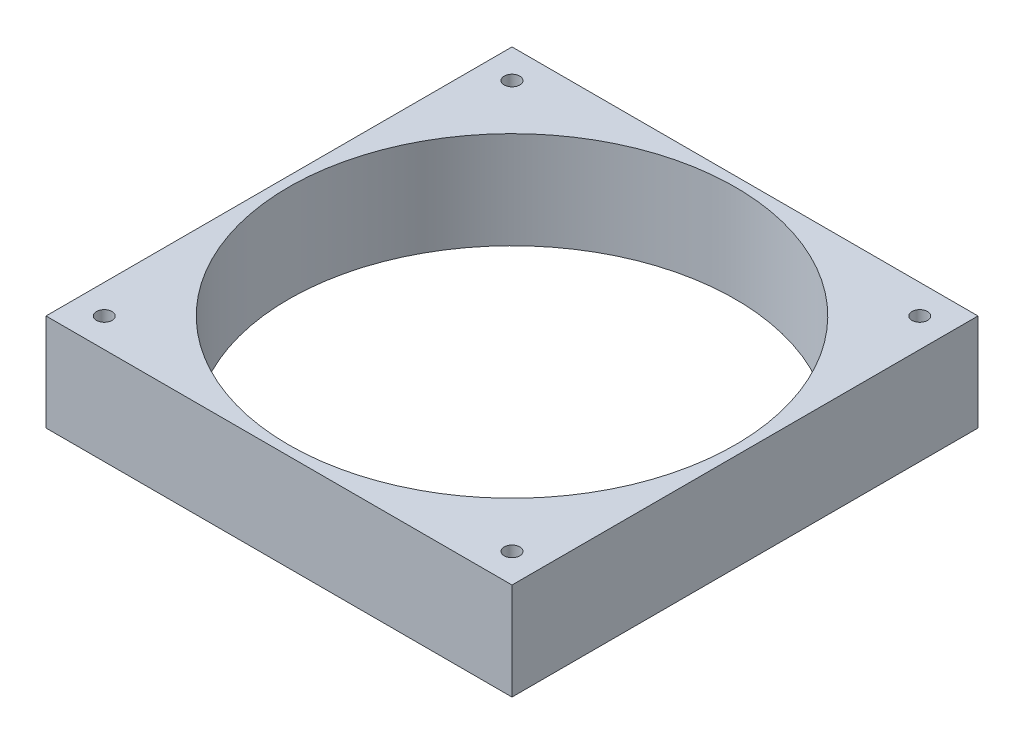
SolidWorks part; units mm, degrees
ref_plane "Front" through (0, 0, 0) normal (0, 0, 1) x (1, 0, 0)
ref_plane "Top" through (0, 0, 0) normal (0, 1, 0) x (1, 0, 0)
ref_plane "Right" through (0, 0, 0) normal (1, 0, 0) x (0, 0, -1)
sketch "Sketch1" plane through (0, 0, 0) normal (0, 1, 0) x (1, 0, 0)
  line L1 (0, 0) -> (120, 0)
  line L2 (0, 0) -> (0, -120)
  line L3 (0, -120) -> (120, -120)
  line L4 (120, 0) -> (120, -120)
  dimension "D1" = 120
  dimension "D2" = 120
extrude "Boss-Extrude1" add sketch "Sketch1" along normal blind 25
sketch "Sketch2" plane through (0, 25, 0) normal (0, 1, 0) x (1, 0, 0)
  line L0 (0, -120) -> (120, -120) construction
  line L1 (0, 0) -> (0, -120) construction
  circle A0 centre (7.5, -112.5) radius 2
  circle A1 centre (112.5, -112.5) radius 2
  circle A2 centre (112.5, -7.5) radius 2
  circle A3 centre (7.5, -7.5) radius 2
  dimension "D5" = 4
  dimension "D1" = 7.5
  dimension "D2" = 7.5
  dimension "D3" = 2
  dimension "D4" = 2
extrude "Cut-Extrude1" cut sketch "Sketch2" against normal through all
sketch "草图1" plane through (0, 25, 0) normal (0, 1, 0) x (1, 0, 0)
  circle A0 centre (60, -60) radius 57.5
  dimension "D1" = 115
extrude "切除-拉伸1" cut sketch "草图1" against normal blind 100
